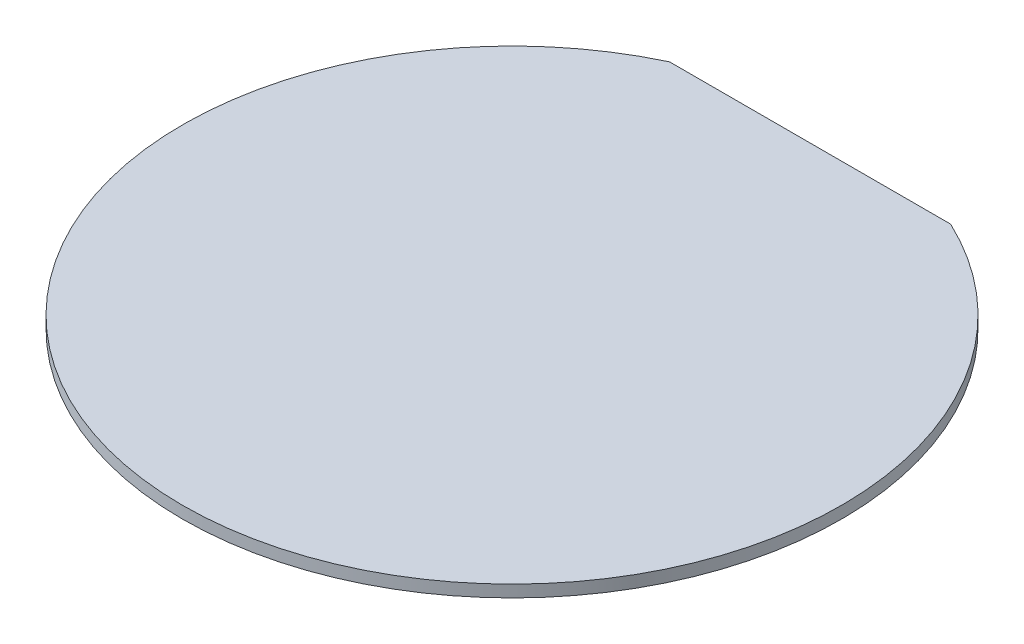
SolidWorks part; units mm, degrees
material "PTFE (general)"
ref_plane "Front Plane" through (0, 0, 0) normal (0, 0, 1) x (1, 0, 0)
ref_plane "Top Plane" through (0, 0, 0) normal (0, 1, 0) x (1, 0, 0)
ref_plane "Right Plane" through (0, 0, 0) normal (1, 0, 0) x (0, 0, -1)
sketch "Sketch1" plane through (0, 0, 0) normal (0, 1, 0) x (-1, 0, 0)
  line L0 (-9.6753, -3.4841) -> (1.8247, -3.4841) construction
  line L1 (-9.6753, -3.4841) -> (-21.1753, -3.4841) construction
  line L2 (-21.1753, -3.4841) -> (-21.1753, -27.3477) construction
  line L3 (1.8247, -3.4841) -> (1.8247, -27.3477) construction
  line L5 (-21.4051, -28.3637) -> (2.0544, -28.3637)
  arc A1 (2.0544, -28.3637) -> (-21.4051, -28.3637) centre (-9.6753, -3.4841) ccw
  dimension "D1" = 11.5
  dimension "D2" = 11.5
extrude "Boss-Extrude1" add sketch "Sketch1" along normal blind 1
